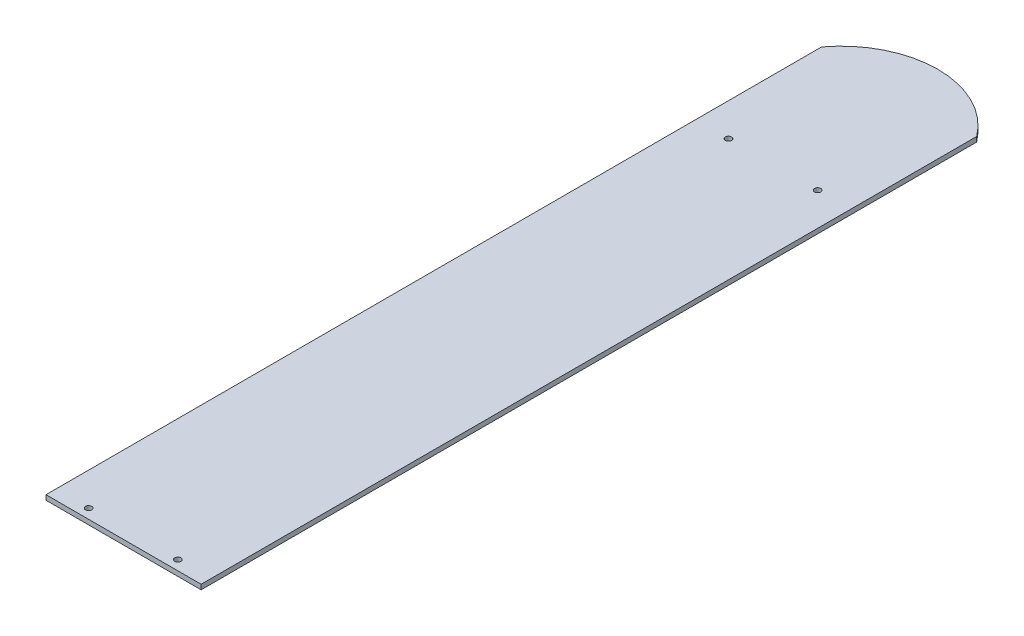
SolidWorks part; units mm, degrees
ref_plane "Front Plane" through (0, 0, 0) normal (0, 0, 1) x (1, 0, 0)
ref_plane "Top Plane" through (0, 0, 0) normal (0, 1, 0) x (1, 0, 0)
ref_plane "Right Plane" through (0, 0, 0) normal (1, 0, 0) x (0, 0, -1)
sketch "Sketch1" plane through (0, 0, 0) normal (0, 1, 0) x (1, 0, 0)
  line L2 (0, 0) -> (0, -508)
  line L3 (0, -508) -> (101.6, -508)
  line L4 (101.6, 0) -> (101.6, -508)
  arc A0 (0, 0) -> (101.6, 0) centre (50.8, -38.1) cw
  dimension "D3" = 63.5
  dimension "D1" = 508
  dimension "D2" = 101.6
extrude "Boss-Extrude1" add sketch "Sketch1" along normal blind 3.175
sketch "Sketch2" plane through (0, 0, 0) normal (0, -1, 0) x (1, 0, 0)
  line L0 (21.59, 82.55) -> (80.01, 82.55) construction
  line L1 (0, 508) -> (101.6, 508) construction
  circle A0 centre (21.59, 501.65) radius 2.032
  circle A1 centre (80.01, 501.65) radius 2.032
  circle A2 centre (21.59, 82.55) radius 2.032
  circle A3 centre (80.01, 82.55) radius 2.032
  arc A4 (0, 0) -> (101.6, 0) centre (50.8, 38.1) ccw construction
  point P11 (50.8, -25.4)
  point P12 (50.8, 82.55)
  dimension "D1" = 4.064
  dimension "D2" = 58.42
  dimension "D3" = 6.35
  dimension "D4" = 419.1
extrude "Cut-Extrude1" cut sketch "Sketch2" against normal through all
scale "Scale1" scale about centroid uniform scaling yes scale factor 0.25
